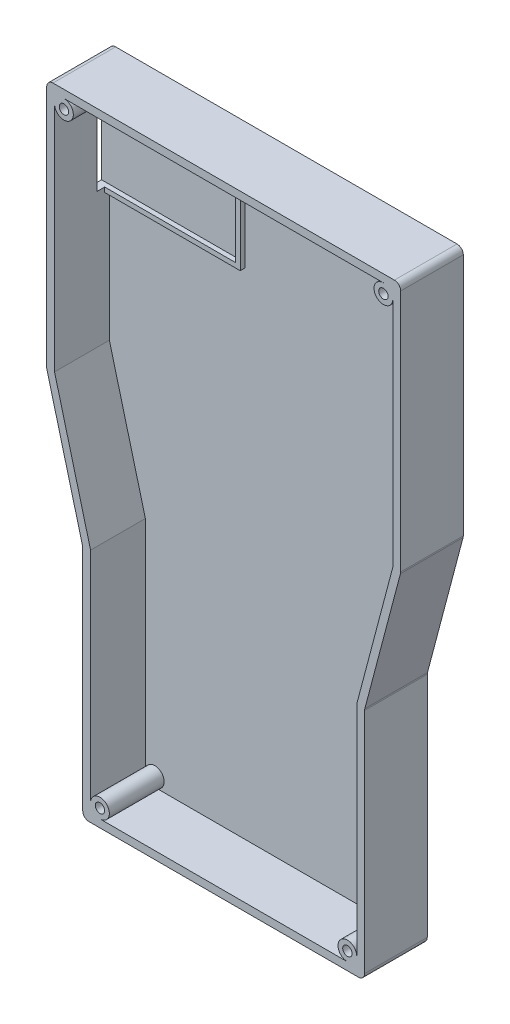
SolidWorks part; units mm, degrees
ref_plane "Front Plane" through (0, 0, 0) normal (0, 0, 1) x (1, 0, 0)
ref_plane "Top Plane" through (0, 0, 0) normal (0, 1, 0) x (1, 0, 0)
ref_plane "Right Plane" through (0, 0, 0) normal (1, 0, 0) x (0, 0, -1)
sketch "Sketch1" plane through (0, 0, 0) normal (0, 0, 1) x (1, 0, 0)
  line L0 (0, -1001.1888) -> (0, 48998.8112) construction
  line L6 (-45, -123.475) -> (-45, -198.475)
  line L7 (-56.5, -79.95) -> (-45, -123.475)
  line L11 (-56.5, 0) -> (-56.5, -79.95)
  line L19 (-56.5, 0) -> (56.5, 0)
  line L30 (56.5, 0) -> (56.5, -79.95)
  line L31 (56.5, -79.95) -> (45, -123.475)
  line L32 (45, -123.475) -> (45, -198.475)
  line L33 (45, -198.475) -> (-45, -198.475)
  point P51 (0, 0)
  point P56 (0, -198.475)
  dimension "D1" = 113
  dimension "D2" = 79.95
  dimension "D3" = 75
  dimension "D4" = 45
  dimension "D5" = 198.475
extrude "Boss-Extrude1" add sketch "Sketch1" along normal blind 20
shell "Shell1" thickness 2.5
fillet "Fillet1" radius 2 8 edges at (45, -123.475, 10) (56.5, -79.95, 10) (45, -198.475, 10) (-45, -198.475, 10) (-56.5, -79.95, 10) (-45, -123.475, 10) (-56.5, 0, 10) (56.5, 0, 10)
sketch "Sketch2" plane through (0, 0, 2.5) normal (0, 0, 1) x (1, 0, 0)
  line L0 (0, -1000) -> (0, 49000) construction
  line L1 (54, -2.5) -> (-54, -2.5) construction
  line L2 (54, -79.6253) -> (54, -2.5) construction
  line L3 (42.5, -195.975) -> (42.5, -123.1503) construction
  line L4 (-42.5, -195.975) -> (42.5, -195.975) construction
  line L6 (54, -5.5) -> (54, -2.5)
  line L7 (54, -2.5) -> (51, -2.5)
  line L8 (42.5, -195.975) -> (42.5, -192.975)
  line L9 (-39.5, -195.975) -> (-42.5, -195.975)
  line L10 (-42.5, -195.975) -> (-42.5, -192.975)
  line L11 (39.5, -195.975) -> (42.5, -195.975)
  line L12 (-54, -2.5) -> (-51, -2.5)
  line L13 (-54, -5.5) -> (-54, -2.5)
  arc A0 (51, -2.5) -> (54, -5.5) centre (51, -5.5) ccw
  arc A1 (42.5, -192.975) -> (39.5, -195.975) centre (39.5, -192.975) ccw
  arc A5 (-42.5, -192.975) -> (-39.5, -195.975) centre (-39.5, -192.975) cw
  arc A6 (-51, -2.5) -> (-54, -5.5) centre (-51, -5.5) cw
  dimension "D1" = 6
extrude "Boss-Extrude2" add sketch "Sketch2" along normal through all
sketch "Sketch4" plane through (0, 0, 20) normal (0, 0, 1) x (1, 0, 0)
  line L0 (0, -1000) -> (0, 49000) construction
  circle A0 centre (51, -5.5) radius 1.5
  circle A1 centre (39.5, -192.975) radius 1.5
  circle A2 centre (-39.5, -192.975) radius 1.5
  circle A3 centre (-51, -5.5) radius 1.5
  dimension "D1" = 3
extrude "Cut-Extrude1" cut sketch "Sketch4" against normal through all
sketch "Sketch5" plane through (0, 0, 2.5) normal (0, 0, 1) x (1, 0, 0)
  line L0 (-54, -5.5) -> (-54, -79.6253) construction
  line L1 (-54, -12.5) -> (-12.2, -12.5)
  line L2 (-54, -12.5) -> (-54, -36.5)
  line L3 (-54, -36.5) -> (-12.2, -36.5)
  line L4 (-12.2, -12.5) -> (-12.2, -36.5)
  line L5 (51, -2.5) -> (-51, -2.5) construction
  line L6 (-54, -11) -> (-10.7, -11)
  line L7 (-10.7, -11) -> (-10.7, -38)
  line L8 (-54, -38) -> (-10.7, -38)
  line L9 (-54, -11) -> (-54, -12.5)
  line L10 (-54, -38) -> (-54, -36.5)
  line M6 (-54, -5.5) -> (-54, -79.6253)
  dimension "D1" = 41.8
  dimension "D2" = 24
  dimension "D3" = 10
  dimension "D4" = 1.5
extrude "Boss-Extrude3" add sketch "Sketch5" along normal blind 1.5 contours L8 L7 L6 L1 L4 L3 M6
sketch "Sketch6" plane through (-56.5, 0, 0) normal (-1, 0, 0) x (0, 0, 1)
  line L0 (4, -36.5) -> (2.5, -36.5) construction
  line L1 (2.5, -12.5) -> (6.5, -12.5)
  line L2 (2.5, -12.5) -> (2.5, -36.5)
  line L3 (2.5, -36.5) -> (6.5, -36.5)
  line L4 (6.5, -12.5) -> (6.5, -36.5)
  dimension "D1" = 4
extrude "Cut-Extrude2" cut sketch "Sketch6" against normal up to next
